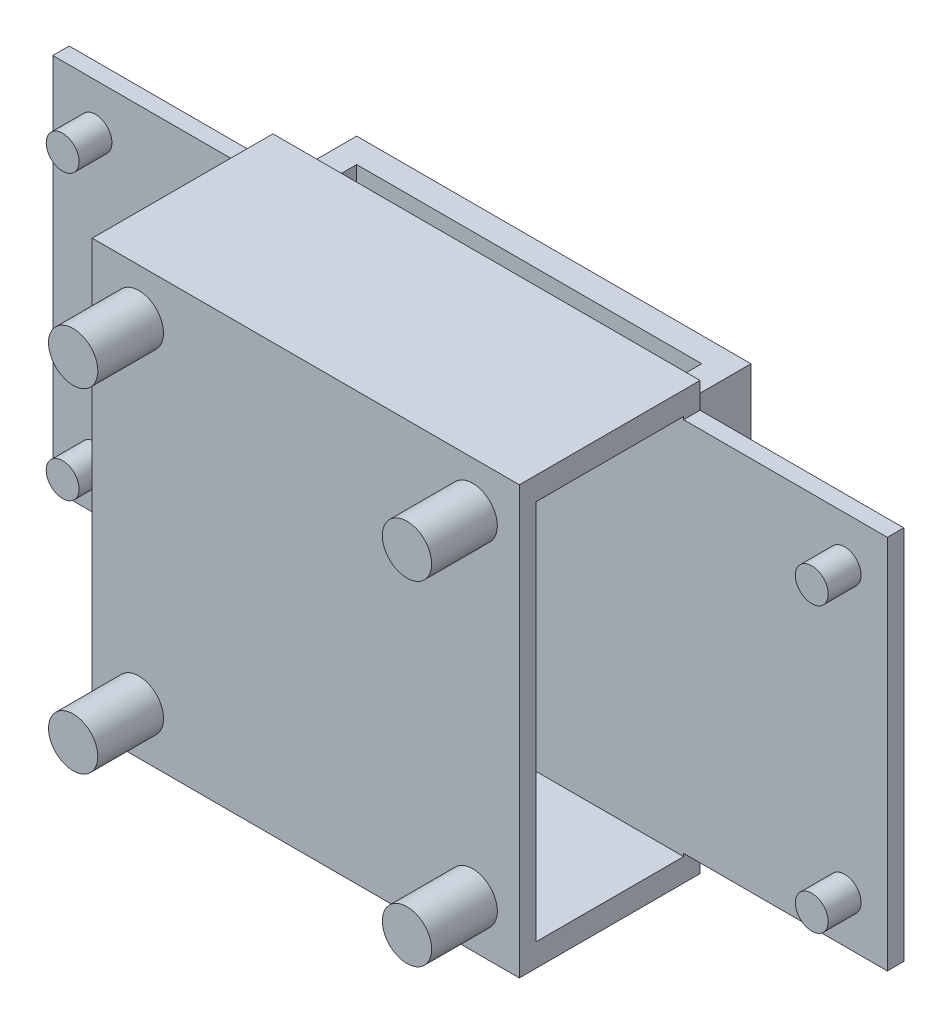
SolidWorks part; units mm, degrees
ref_plane "前视基准面" through (0, 0, 0) normal (0, 0, 1) x (1, 0, 0)
ref_plane "上视基准面" through (0, 0, 0) normal (0, 1, 0) x (1, 0, 0)
ref_plane "右视基准面" through (0, 0, 0) normal (1, 0, 0) x (0, 0, -1)
sketch "草图1" plane through (0, 0, 0) normal (0, 0, 1) x (1, 0, 0)
  line L0 (-13, -11.43) -> (-13, -13)
  line L1 (-25.4, 11.43) -> (-13, 11.43)
  line L2 (-25.4, 11.43) -> (-25.4, -11.43)
  line L3 (-25.4, -11.43) -> (-13, -11.43)
  line L4 (25.4, 11.43) -> (25.4, -11.43)
  line L5 (-25.4, 11.43) -> (25.4, -11.43) construction
  line L6 (-25.4, -11.43) -> (25.4, 11.43) construction
  line L7 (-13, 13) -> (13, 13)
  line L8 (-13, 13) -> (-13, 11.43)
  line L9 (-13, -13) -> (13, -13)
  line L10 (13, 13) -> (13, 11.43)
  line L11 (-13, 13) -> (13, -13) construction
  line L12 (-13, -13) -> (13, 13) construction
  line L13 (13, -11.43) -> (25.4, -11.43)
  line L14 (13, -11.43) -> (13, -13)
  line L15 (13, 11.43) -> (25.4, 11.43)
  point P0 (0, 0)
  point P6 (0, 0)
extrude "凸台-拉伸1" add sketch "草图1" along normal blind 1
sketch "草图3" plane through (0, 0, 1) normal (0, 0, 1) x (1, 0, 0)
  line L0 (-25.4, -11.43) -> (-22.8, -11.43) construction
  line L1 (-25.4, -11.43) -> (-13, -11.43) construction
  line L2 (-22.8, -11.43) -> (-22.8, -8.63) construction
  line L3 (0, 0) -> (-2, 0) construction
  line L4 (0, 0) -> (0, 2) construction
  circle A0 centre (-22.8, -8.63) radius 1
  circle A1 centre (-22.8, 8.63) radius 1
  circle A2 centre (22.8, -8.63) radius 1
  circle A3 centre (22.8, 8.63) radius 1
extrude "凸台-拉伸2" add sketch "草图3" along normal blind 2
sketch "草图6" plane through (0, 0, 0) normal (0, 0, -1) x (-1, 0, 0)
  line L0 (19.2, 11.43) -> (-12.1, 11.43) construction
  line L1 (13, 11.43) -> (25.4, 11.43) construction
  line L2 (19.2, 11.43) -> (10.5, 11.43) construction
  line L3 (0, 0) -> (4, 0) construction
  line L4 (-12.1, 11.43) -> (11.9, 11.43)
  line L5 (-12.1, 11.43) -> (-12.1, 7.43)
  line L6 (-12.1, 7.43) -> (11.9, 7.43)
  line L7 (11.9, 11.43) -> (11.9, 7.43)
  line L8 (-12.1, -7.43) -> (11.9, -7.43)
  line L9 (11.9, -11.43) -> (11.9, -7.43)
  line L10 (-12.1, -11.43) -> (11.9, -11.43)
  line L11 (-12.1, -11.43) -> (-12.1, -7.43)
sketch "草图9" plane through (0, 0, 1) normal (0, 0, 1) x (1, 0, 0)
  line L0 (0, 0) -> (3, 0) construction
  line L1 (-13, 13) -> (13, 13)
  line L2 (-13, 13) -> (-13, 11.6)
  line L3 (-13, 11.6) -> (13, 11.6)
  line L4 (13, 13) -> (13, 11.6)
  line L5 (-13, -11.6) -> (13, -11.6)
  line L6 (13, -13) -> (13, -11.6)
  line L7 (-13, -13) -> (13, -13)
  line L8 (-13, -13) -> (-13, -11.6)
extrude "凸台-拉伸4" add sketch "草图9" along normal blind 9
sketch "草图10" plane through (0, 0, 10) normal (0, 0, 1) x (1, 0, 0)
  line L1 (-13, 13) -> (13, 13)
  line L2 (-13, 13) -> (-13, -13)
  line L3 (-13, -13) -> (13, -13)
  line L4 (13, 13) -> (13, -13)
extrude "凸台-拉伸5" add sketch "草图10" along normal blind 1
sketch "草图11" plane through (0, 0, 11) normal (0, 0, 1) x (1, 0, 0)
  line L0 (-12.7, -12.7) -> (-10.16, -12.7) construction
  line L1 (-12.7, 12.7) -> (12.7, 12.7) construction
  line L2 (-12.7, 12.7) -> (-12.7, -12.7) construction
  line L3 (-12.7, -12.7) -> (12.7, -12.7) construction
  line L4 (12.7, 12.7) -> (12.7, -12.7) construction
  line L5 (-12.7, 12.7) -> (12.7, -12.7) construction
  line L6 (-12.7, -12.7) -> (12.7, 12.7) construction
  line L7 (-10.16, -12.7) -> (-10.16, -10.16) construction
  line L8 (0, 0) -> (4, 0) construction
  line L9 (0, 0) -> (0, 4) construction
  circle A0 centre (-10.16, -10.16) radius 1.5
  circle A1 centre (10.16, -10.16) radius 1.5
  circle A2 centre (10.16, 10.16) radius 1.5
  circle A3 centre (-10.16, 10.16) radius 1.5
  point P0 (0, 0)
extrude "凸台-拉伸6" add sketch "草图11" along normal blind 4
extrude "凸台-拉伸7" add sketch "草图6" along normal blind 4
sketch "草图12" plane through (0, -11.43, 0) normal (0, -1, 0) x (-1, 0, 0)
  line L0 (11.9, 4) -> (10.4, 4) construction
  line L1 (-12.1, 4) -> (11.9, 4) construction
  line L2 (10.4, 4) -> (10.4, 2.5) construction
  line L4 (10.4, 2.5) -> (-10.6, 2.5)
  line L5 (10.4, 2.5) -> (10.4, 0.5)
  line L6 (10.4, 0.5) -> (-10.6, 0.5)
  line L7 (-10.6, 2.5) -> (-10.6, 0.5)
extrude "切除-拉伸3" cut sketch "草图12" against normal blind 25
